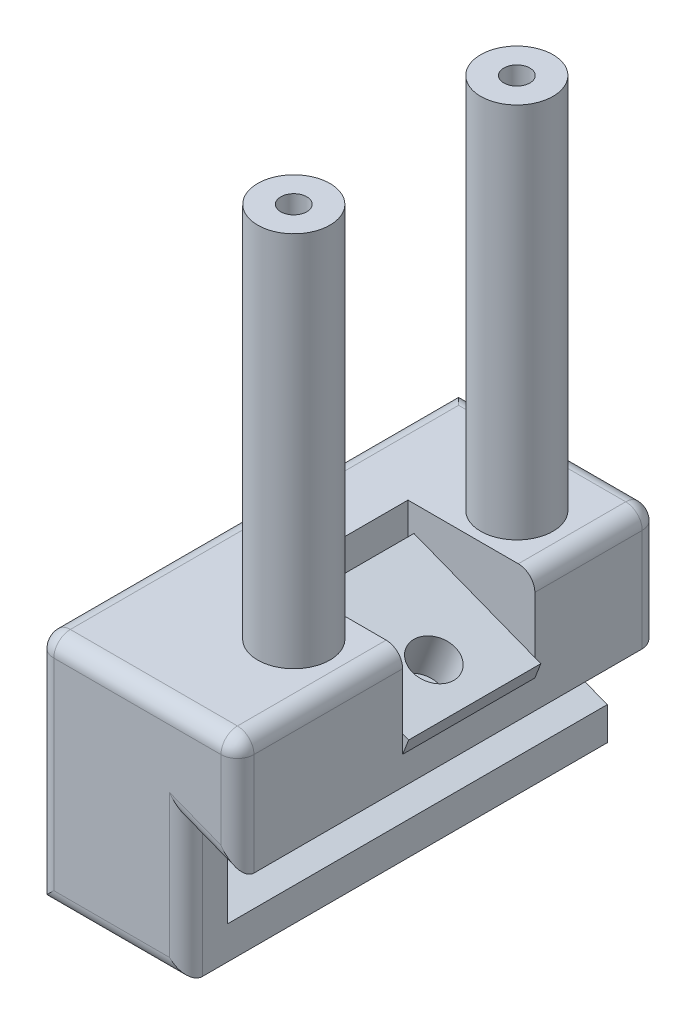
SolidWorks part; units mm, degrees
other "Markup1"
sketch "Sketch10" plane through (30.7748, 80.4925, 62.23) normal (0.2074, 0.1155, 0.9714) x (0.96, 0.1671, -0.2249)
ref_plane "Front Plane" through (0, 0, 0) normal (0, 0, 1) x (1, 0, 0)
ref_plane "Top Plane" through (0, 0, 0) normal (0, 1, 0) x (1, 0, 0)
ref_plane "Right Plane" through (0, 0, 0) normal (1, 0, 0) x (0, 0, -1)
sketch "Sketch1" plane through (0, 0, 0) normal (0, 0, 1) x (1, 0, 0)
  line L0 (0, 0) -> (22.86, 0)
  line L1 (22.86, 0) -> (22.86, 5.08)
  line L2 (22.86, 5.08) -> (0, 13.97)
  line L3 (0, 13.97) -> (0, 0)
  dimension "D1" = 22.86
  dimension "D2" = 13.97
  dimension "D3" = 5.08
extrude "Boss-Extrude1" add sketch "Sketch1" along normal blind 58.42
sketch "Sketch2" plane through (0, 0, 58.42) normal (0, 0, 1) x (1, 0, 0)
  line L0 (0, 0) -> (0, 29.6925)
  line L1 (0, 29.6925) -> (22.86, 29.6925)
  line L2 (22.86, 29.6925) -> (22.86, 0)
  line L3 (0, 0) -> (22.86, 0) construction
  line L4 (22.86, 0) -> (0, 0)
extrude "Boss-Extrude2" add sketch "Sketch2" along normal blind 6.35
sketch "Sketch3" plane through (0, 0, 58.42) normal (0, 0, -1) x (-1, 0, 0)
  line L0 (-22.86, 29.6925) -> (0, 29.6925)
  line L1 (-22.86, 29.6925) -> (0, 29.6925) construction
  line L2 (0, 29.6925) -> (-30.7748, 17.7245)
  line L4 (-30.7748, 17.7245) -> (-30.7748, 29.6925)
  line L5 (-22.86, 5.08) -> (0, 13.97) construction
  line L7 (-30.7748, 29.6925) -> (-22.86, 29.6925)
  dimension "D1" = 33.02
extrude "Boss-Extrude3" add sketch "Sketch3" along normal blind 58.42 contours L7 L0 L2 L4
sketch "Sketch5" plane through (0, 0, 0) normal (0, 0, -1) x (-1, 0, 0)
  line L0 (-30.7748, 22.1078) -> (-11.2714, 29.6925)
  line L1 (-30.7748, 17.7245) -> (-30.7748, 29.6925) construction
  line L3 (0, 29.6925) -> (-22.86, 20.8025) construction
  line L4 (-30.7748, 29.6925) -> (0, 29.6925) construction
  line L5 (-11.2714, 29.6925) -> (-30.7748, 29.6925)
  line L6 (-30.7748, 29.6925) -> (-30.7748, 22.1078)
extrude "Cut-Extrude1" cut sketch "Sketch5" against normal blind 58.42
sketch "Sketch6" plane through (0, 0, 0) normal (0, 0, -1) x (-1, 0, 0)
  line L0 (-11.2714, 29.6925) -> (-30.7748, 29.6925)
  line L1 (-30.7748, 29.6925) -> (-30.7748, 22.1078)
  line L2 (-30.7748, 22.1078) -> (-11.2714, 29.6925)
extrude "Boss-Extrude5" add sketch "Sketch6" against normal blind 19.05 separate body contours L1 L2 L0
sketch "Sketch7" plane through (0, 0, 58.42) normal (0, 0, 1) x (1, 0, 0)
  line L0 (30.7748, 22.1078) -> (30.7748, 29.6925)
  line L1 (30.7748, 29.6925) -> (11.2714, 29.6925)
  line L2 (11.2714, 29.6925) -> (30.7748, 22.1078)
extrude "Boss-Extrude6" add sketch "Sketch7" against normal blind 19.05
sketch "Sketch8" plane through (11.5109, 29.5994, 0) normal (0.3624, 0.932, 0) x (0.932, -0.3624, 0)
  line L1 (-10.7619, 0) -> (-10.7619, -58.42) construction
  line L2 (-10.7619, -29.21) -> (20.6693, -29.21) construction
  line L3 (20.6693, -39.37) -> (20.6693, 0) construction
  circle A0 centre (13.9233, -29.21) radius 3.3
  dimension "D1" = 6.6
  dimension "D2" = 0
  dimension "D3" = 6.746
extrude "Cut-Extrude2" cut sketch "Sketch8" against normal up to next (4.0853 mm away)
sketch "Sketch9" plane through (0, 29.6925, 0) normal (0, 1, 0) x (1, 0, 0)
  line L0 (21.0231, -39.37) -> (21.0231, -64.77) construction
  line L1 (11.2714, -39.37) -> (30.7748, -39.37) construction
  line L2 (22.86, -64.77) -> (0, -64.77) construction
  line L5 (0, 0) -> (0, -58.42) construction
  line L7 (21.0231, -19.05) -> (21.0231, 0) construction
  line L8 (11.2714, -19.05) -> (30.7748, -19.05) construction
  line L9 (11.2714, 0) -> (30.7748, 0) construction
  line L10 (0, -29.21) -> (36.4511, -29.21) construction
  circle A0 centre (21.0231, -12.065) radius 5.5562
  circle A1 centre (21.0231, -46.355) radius 5.5563
  dimension "D1" = 11.1125
  dimension "D2" = 11.1125
  dimension "D3" = 17.145
  dimension "D4" = 17.145
extrude "Boss-Extrude7" add sketch "Sketch9" along normal blind 64.262
sketch "Sketch11" plane through (0, 93.9545, 0) normal (0, 1, 0) x (1, 0, 0)
  circle A0 centre (21.0231, -12.065) radius 2
  circle A1 centre (21.0231, -46.355) radius 2
  dimension "D1" = 4
  dimension "D2" = 4
extrude "Cut-Extrude3" cut sketch "Sketch11" against normal blind 7
sketch "Sketch12" plane through (0, 0, 58.42) normal (0, 0, 1) x (1, 0, 0)
  line L0 (22.86, 29.6925) -> (30.7748, 29.6925)
  line L1 (30.7748, 29.6925) -> (30.7748, 17.7245)
  line L2 (30.7748, 17.7245) -> (22.86, 20.8025)
  line L3 (22.86, 20.8025) -> (22.86, 29.6925)
extrude "Boss-Extrude8" add sketch "Sketch12" along normal up to surface (6.35 mm away) up to face at (11.43, 14.8462, 64.77)
sketch "Sketch14" plane through (0, 29.6925, 0) normal (0, 1, 0) x (1, 0, 0)
  line L0 (0, 0) -> (0, -64.77)
  line L1 (0, -64.77) -> (30.7748, -64.77)
  line L2 (30.7748, -64.77) -> (30.7748, -39.37)
  line L3 (30.7748, -39.37) -> (11.2714, -39.37)
  line L4 (11.2714, -39.37) -> (11.2714, -19.05)
  line L5 (11.2714, -19.05) -> (30.7748, -19.05)
  line L6 (30.7748, -19.05) -> (30.7748, 0)
  line L7 (30.7748, 0) -> (0, 0)
extrude "Boss-Extrude9" add sketch "Sketch14" along normal blind 6.35
fillet "Fillet3" radius 2.54 12 edges at (0, 18.0212, 64.77) (15.3874, 36.0425, 64.77) (30.7748, 26.8835, 0) (30.7748, 26.8835, 64.77) (26.8174, 19.2635, 64.77) (22.86, 10.4012, 64.77) (11.43, 0, 64.77) (0, 6.985, 0) (15.3874, 36.0425, 0) (0, 36.0425, 32.385) (30.7748, 36.0425, 52.07) (30.7748, 36.0425, 9.525)
sketch "Sketch15" plane through (11.5109, 29.5994, 0) normal (0.3624, 0.932, 0) x (0.932, -0.3624, 0)
  line L1 (20.6693, -19.05) -> (-0.2569, -19.05)
  line L2 (20.6693, -19.05) -> (20.6693, -39.37)
  line L3 (20.6693, -39.37) -> (-0.2569, -39.37)
  line L4 (-0.2569, -19.05) -> (-0.2569, -39.37)
  circle A0 centre (13.9233, -29.21) radius 3.3
extrude "Boss-Extrude10" add sketch "Sketch15" along normal blind 2.54
